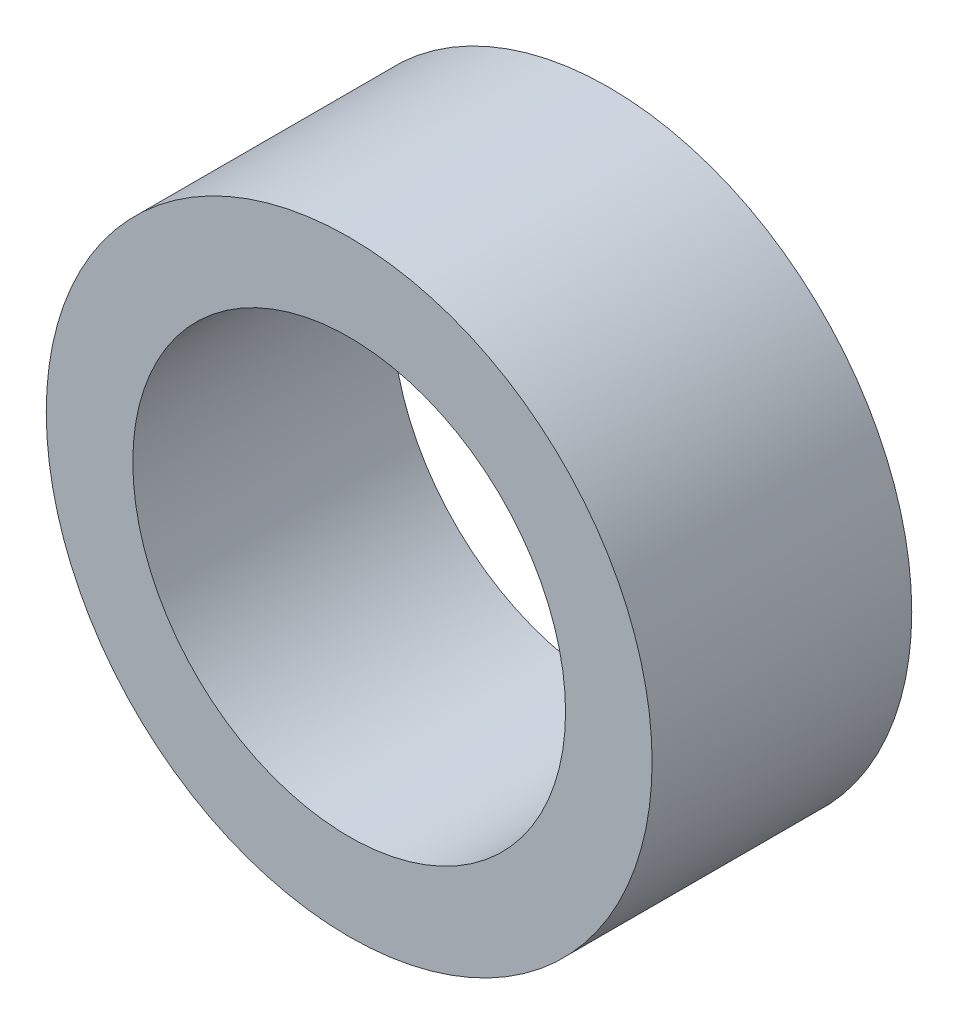
SolidWorks part; units mm, degrees
ref_plane "Front Plane" through (0, 0, 0) normal (0, 0, 1) x (1, 0, 0)
ref_plane "Top Plane" through (0, 0, 0) normal (0, 1, 0) x (1, 0, 0)
ref_plane "Right Plane" through (0, 0, 0) normal (1, 0, 0) x (0, 0, -1)
sketch "Sketch1" plane through (0, 0, 0) normal (0, 0, 1) x (1, 0, 0)
  circle A0 centre (0, 0) radius 2.5
  circle A1 centre (0, 0) radius 3.5
  dimension "D1" = 5
  dimension "D2" = 7
extrude "Boss-Extrude1" add sketch "Sketch1" along normal blind 3
